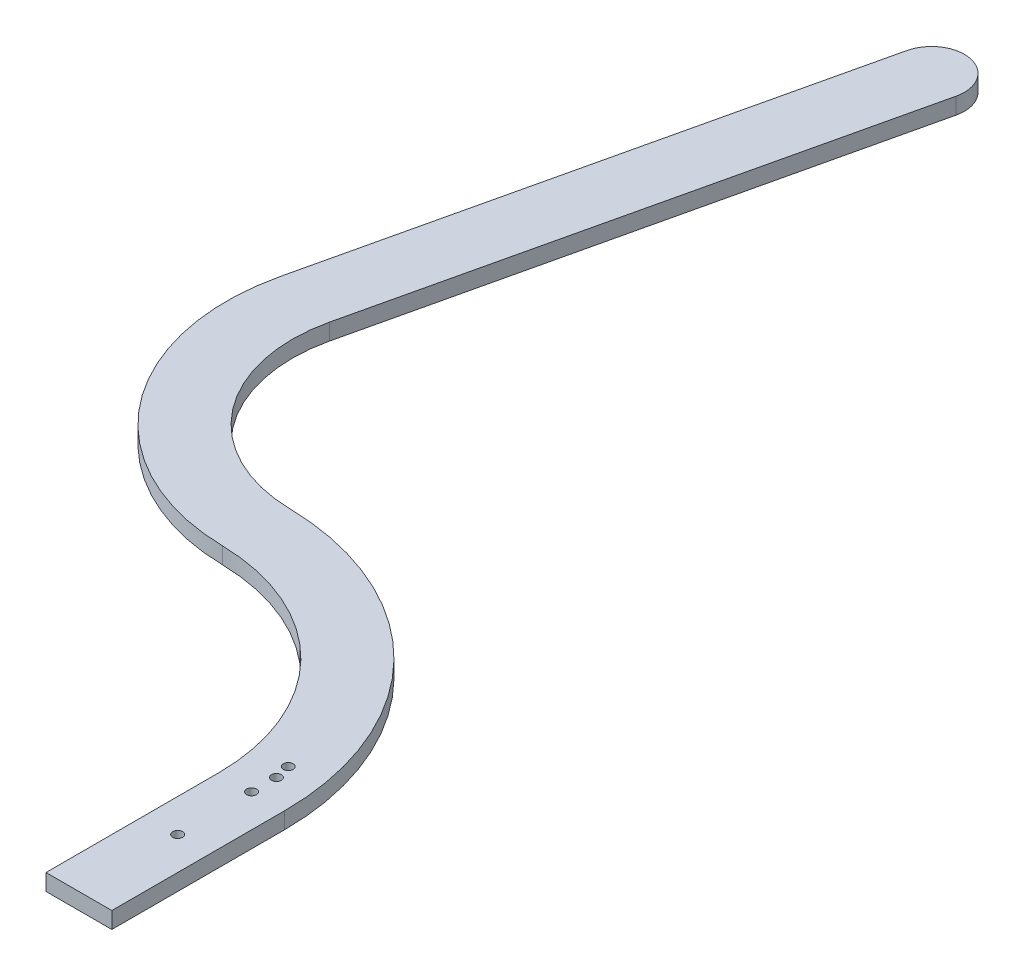
SolidWorks part; units mm, degrees
ref_plane "前基準面" through (0, 0, 0) normal (0, 0, 1) x (1, 0, 0)
ref_plane "上基準面" through (0, 0, 0) normal (0, 1, 0) x (1, 0, 0)
ref_plane "右基準面" through (0, 0, 0) normal (1, 0, 0) x (0, 0, -1)
sketch "草圖1" plane through (0, 0, 0) normal (0, 1, 0) x (1, 0, 0)
  line L0 (-27.5955, 169.2679) -> (-8.1091, 164.7646) construction
  line L1 (57.8974, -125.2996) -> (57.8974, -177.7436)
  line L2 (57.8974, -177.7436) -> (77.8974, -177.7436)
  line L3 (77.8974, -177.7436) -> (77.8974, -125.2996)
  line L4 (-0.871, -44.9916) -> (-1.2581, -64.9878) construction
  line L5 (-63.3309, 14.6357) -> (-27.5955, 169.2679)
  line L6 (-8.1091, 164.7646) -> (-43.8444, 10.1324)
  line L7 (57.8974, -125.2996) -> (77.8974, -125.2996) construction
  circle A0 centre (0, 0) radius 45 construction
  arc A2 (-27.5955, 169.2679) -> (-8.1091, 164.7646) centre (-17.8523, 167.0163) cw
  arc A3 (-63.3309, 14.6357) -> (-1.2581, -64.9878) centre (0, 0) ccw
  arc A4 (-1.2581, -64.9878) -> (57.8974, -125.2996) centre (-2.4257, -125.2996) cw
  arc A5 (77.8974, -125.2996) -> (-0.871, -44.9916) centre (-2.4257, -125.2996) ccw
  arc A6 (-0.871, -44.9916) -> (-43.8444, 10.1324) centre (0, 0) cw
  arc A8 (-1.0646, -54.9897) -> (67.8974, -125.2996) centre (-2.4257, -125.2996) cw construction
  circle A9 centre (66.829, -113.0881) radius 1.5
  circle A10 centre (67.8974, -125.2996) radius 1.5
  dimension "D1" = 90
  dimension "D2" = 20
  dimension "D4" = 3
  dimension "D5" = 3
  dimension "D3" = 20
  dimension "D6" = 10
extrude "伸長1" add sketch "草圖1" along normal blind 5
sketch "草圖2" plane through (0, 5, 0) normal (0, 1, 0) x (1, 0, 0)
  line L0 (67.8974, -177.7436) -> (67.8974, -117.7436) construction
  line L1 (57.8974, -177.7436) -> (77.8974, -177.7436) construction
  circle A0 centre (67.8974, -117.7436) radius 1.5
  circle A1 centre (67.8974, -147.7436) radius 1.5
  dimension "D2" = 3
  dimension "D3" = 3
  dimension "D1" = 30
extrude "伸長2" cut sketch "草圖2" against normal through all
